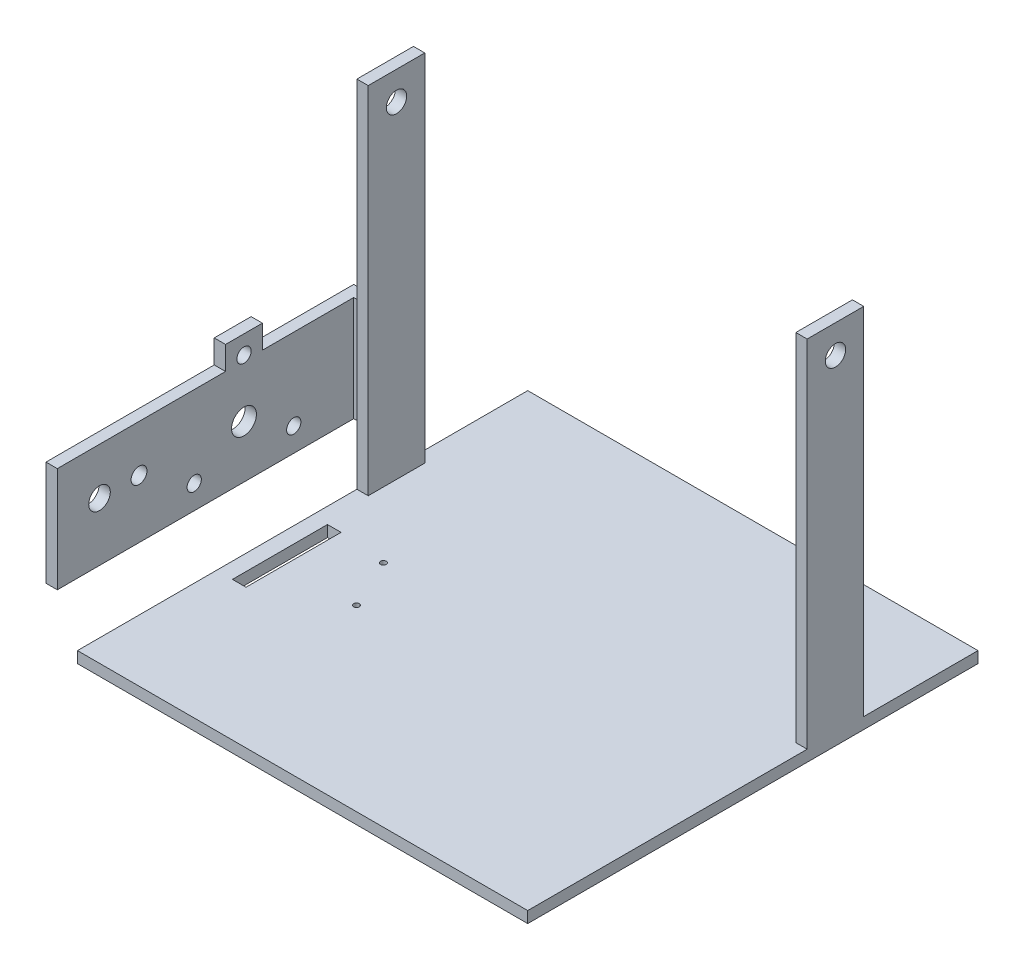
SolidWorks part; units mm, degrees
material "AISI 316 Stainless Steel Sheet (SS)"
ref_plane "Front Plane" through (0, 0, 0) normal (0, 0, 1) x (1, 0, 0)
ref_plane "Top Plane" through (0, 0, 0) normal (0, 1, 0) x (1, 0, 0)
ref_plane "Right Plane" through (0, 0, 0) normal (1, 0, 0) x (0, 0, -1)
sketch "Sketch1" plane through (0, 0, 0) normal (0, 1, 0) x (1, 0, 0)
  line L0 (0, 0) -> (199, 0)
  line L1 (199, 0) -> (199, -199)
  line L2 (199, -199) -> (0, -199)
  line L3 (0, -199) -> (0, 0)
  dimension "D1" = 199
  dimension "D2" = 199
extrude "Boss-Extrude1" add sketch "Sketch1" along normal blind 5
sketch "Sketch2" plane through (0, 5, 0) normal (0, 1, 0) x (1, 0, 0)
  line L0 (0, -50.5) -> (0, -75.5)
  line L1 (0, 0) -> (0, -199) construction
  line L2 (0, -75.5) -> (5, -75.5)
  line L3 (5, -75.5) -> (5, -50.5)
  line L4 (5, -50.5) -> (0, -50.5)
  dimension "D1" = 25
  dimension "D2" = 50.5
  dimension "D3" = 5
extrude "Boss-Extrude2" add sketch "Sketch2" along normal blind 18.8
sketch "Sketch3" plane through (0, 23.8, 0) normal (0, 1, 0) x (1, 0, 0)
  line L0 (5, -50.5) -> (5, -75.5)
  line L1 (5, -75.5) -> (5, -50.5) construction
  line L2 (5, -50.5) -> (0, -50.5) construction
  line L3 (5, -75.5) -> (0, -75.5)
  line L5 (0, -75.5) -> (0, -50.5)
  line L6 (0, -50.5) -> (5, -50.5)
  dimension "D1" = 25
extrude "Boss-Extrude3" add sketch "Sketch3" along normal blind 46.4
sketch "Sketch4" plane through (0, 70.2, 0) normal (0, 1, 0) x (1, 0, 0)
  line L0 (0, -50.5) -> (5, -50.5)
  line L1 (0, -50.5) -> (0, -75.5)
  line L2 (5, -50.5) -> (5, -75.5)
  line L3 (0, -75.5) -> (5, -75.5)
  line L4 (0, -50.5) -> (0, -75.5) construction
  line L5 (5, -50.5) -> (0, -50.5) construction
  line L6 (5, -75.5) -> (5, -50.5) construction
  dimension "D1" = 25
extrude "Boss-Extrude4" add sketch "Sketch4" along normal blind 91.8
sketch "Sketch5" plane through (0, 5, 0) normal (0, 1, 0) x (1, 0, 0)
  line L0 (199, -50.5) -> (194, -50.5)
  line L1 (199, -199) -> (199, 0) construction
  line L2 (194, -50.5) -> (194, -75.5)
  line L3 (194, -75.5) -> (199, -75.5)
  line L4 (199, -75.5) -> (199, -50.5)
  line L5 (5, -50.5) -> (0, -50.5) construction
  line L6 (0, -75.5) -> (5, -75.5) construction
  dimension "D1" = 5
extrude "Boss-Extrude5" add sketch "Sketch5" along normal blind 157
sketch "Sketch6" plane through (0, 0, 0) normal (-1, 0, 0) x (0, 0, 1)
  line L0 (75.5, 162) -> (75.5, 5) construction
  line L1 (50.5, 162) -> (75.5, 162) construction
  circle A0 centre (63, 149.5) radius 4.5
  dimension "D3" = 9
  dimension "D1" = 12.5
  dimension "D2" = 12.5
extrude "Cut-Extrude1" cut sketch "Sketch6" against normal through all
sketch "Sketch8" plane through (0, 0, 0) normal (-1, 0, 0) x (0, 0, 1)
  line L0 (63, 70.2) -> (68, 70.2)
  line L1 (68, 70.2) -> (68, 23.8)
  line L2 (68, 23.8) -> (63, 23.8)
  line L3 (63, 23.8) -> (63, 70.2)
  line L5 (75.5, 162) -> (75.5, 5) construction
  dimension "D1" = 5
  dimension "D2" = 7.5
  dimension "D3" = 46.4
extrude "Boss-Extrude6" add sketch "Sketch8" along normal blind 13.9
sketch "Sketch9" plane through (0, 0, 68) normal (0, 0, 1) x (1, 0, 0)
  line L0 (-13.9, 70.2) -> (-8.9, 70.2)
  line L1 (-13.9, 70.2) -> (-13.9, 23.8)
  line L2 (-8.9, 70.2) -> (-8.9, 23.8)
  line L3 (-13.9, 23.8) -> (-8.9, 23.8)
  line L4 (-13.9, 23.8) -> (-13.9, 70.2) construction
  line L5 (-13.9, 70.2) -> (0, 70.2) construction
  line L7 (-13.9, 23.8) -> (0, 23.8) construction
  dimension "D1" = 5
extrude "Boss-Extrude7" add sketch "Sketch9" along normal blind 131
sketch "Sketch10" plane through (-13.9, 0, 0) normal (-1, 0, 0) x (0, 0, 1)
  line L0 (63, 70.2) -> (63, 23.8) construction
  line L1 (63, 23.8) -> (199, 23.8) construction
  circle A0 centre (116.5, 47) radius 5.5
  circle A1 centre (116.5, 72.4) radius 3.15
  circle A2 centre (138.497, 34.3) radius 3.15
  circle A3 centre (94.503, 34.3) radius 3.15
  circle A4 centre (116.5, 47) radius 25.4 construction
  dimension "D1" = 11
  dimension "D3" = 6.3
  dimension "D5" = 6.3
  dimension "D6" = 6.3
  dimension "D11" = 50.8
  dimension "D2" = 53.5
  dimension "D7" = 23.2
  dimension "D10" = 12.7
sketch "Sketch11" plane through (-13.9, 0, 0) normal (-1, 0, 0) x (0, 0, 1)
  line L0 (108.35, 70.2) -> (124.65, 70.2)
  line L1 (199, 70.2) -> (63, 70.2) construction
  line L2 (124.65, 70.2) -> (124.65, 80.55)
  line L3 (124.65, 80.55) -> (108.35, 80.55)
  line L4 (108.35, 80.55) -> (108.35, 70.2)
  dimension "D1" = 8.15
  dimension "D2" = 8.15
  dimension "D3" = 8.15
extrude "Boss-Extrude8" add sketch "Sketch11" against normal blind 5
extrude "Cut-Extrude2" cut sketch "Sketch10" against normal blind 5
sketch "Sketch12" plane through (0, 5, 0) normal (0, 1, 0) x (1, 0, 0)
  line L0 (7, -95.5) -> (13, -95.5)
  line L1 (13, -95.5) -> (13, -137.5)
  line L2 (13, -137.5) -> (7, -137.5)
  line L3 (7, -137.5) -> (7, -95.5)
  line L4 (0, -75.5) -> (0, -199) construction
  line L5 (199, 0) -> (0, 0) construction
  dimension "D1" = 7
  dimension "D2" = 13
  dimension "D3" = 42
  dimension "D4" = 95.5
extrude "Cut-Extrude3" cut sketch "Sketch12" against normal blind 5
sketch "Sketch14" plane through (0, 5, 0) normal (0, 1, 0) x (1, 0, 0)
  line L0 (13, -137.5) -> (13, -95.5) construction
  circle A0 centre (34, -97.8) radius 1.25
  circle A1 centre (44.3188, -120) radius 1.25
  point P6 (13, -116.5)
  dimension "D1" = 2.5
  dimension "D2" = 2.5
  dimension "D3" = 21
  dimension "D4" = 18.7
  dimension "D5" = 3.5
  dimension "D6" = 10.3187
extrude "Cut-Extrude4" [suppressed] cut sketch "Sketch14" against normal blind 4
thread "Thread1" [suppressed] pitch 0.5 start angle 0, offset 0, length 4, pitch 0.5, diameter 2.5
ref_plane "Plane1" through (21.75, 5, 97.8) normal (0, 0, 1) x (-1, 0, 0)
sketch "Thread Profile1" plane through (21.75, 5, 97.8) normal (0, 0, 1) x (-1, 0, 0)
  line L0 (0, 0) -> (0, 0.5) construction
  line L1 (0, 0) -> (0.2706, 0.1562)
  line L2 (0.2706, 0.1562) -> (0.2706, 0.2187)
  line L3 (0.2706, 0.2187) -> (0, 0.375)
  line L4 (0.2706, 0.1875) -> (0, 0.1875) construction
  line L11 (0, 0) -> (0, 0.375)
  point P2 (0, 0)
  dimension "Pitch" = 0.5
  dimension "Profile_Angle" = 60
  dimension "Profile_Land" = 0.0625
  dimension "Profile_Height" = 0.2706
thread "Thread2" [suppressed] pitch 0.5 start angle 0, offset 0, length 4, pitch 0.5, diameter 2.5
ref_plane "Plane2" through (32.0688, 5, 120) normal (0, 0, 1) x (-1, 0, 0)
sketch "Thread Profile2" plane through (32.0688, 5, 120) normal (0, 0, 1) x (-1, 0, 0)
  line L0 (0, 0) -> (0, 0.5) construction
  line L1 (0, 0) -> (0.2706, 0.1562)
  line L2 (0.2706, 0.1562) -> (0.2706, 0.2187)
  line L3 (0.2706, 0.2187) -> (0, 0.375)
  line L4 (0.2706, 0.1875) -> (0, 0.1875) construction
  line L11 (0, 0) -> (0, 0.375)
  point P2 (0, 0)
  dimension "Pitch" = 0.5
  dimension "Profile_Angle" = 60
  dimension "Profile_Land" = 0.0625
  dimension "Profile_Height" = 0.2706
sketch "Sketch16" [suppressed] plane through (-13.9, 0, 0) normal (-1, 0, 0) x (0, 0, 1)
  circle A0 centre (180.3485, 49.5625) radius 4.7625
extrude "Cut-Extrude6" [suppressed] cut sketch "Sketch16" against normal blind 9
sketch "Sketch17" plane through (-13.9, 0, 0) normal (-1, 0, 0) x (0, 0, 1)
  circle A0 centre (162.886, 49.5625) radius 3.5
  dimension "D1" = 7
extrude "Cut-Extrude7" cut sketch "Sketch17" against normal blind 9
hole_wizard "M3x0.5 Tapped Hole1" positions "Sketch18" profile "Sketch19" tap size "M3x0.5" standard "ANSI Metric"
sketch "Sketch18" plane through (0, 5, 0) normal (0, 1, 0) x (1, 0, 0)
  point P0 (34, -97.8)
  point P3 (44.3188, -120)
sketch "Sketch19" plane through (34, 5, 97.8) normal (1, 0, 0) x (0, 0, 1)
  line L0 (0, 0) -> (0, 8.2511)
  line L1 (0, 8.2511) -> (1.25, 7.5)
  line L2 (1.25, 7.5) -> (1.25, 0)
  line L5 (1.25, 0) -> (0, 0)
  line L10 (0, 8.2511) -> (-1.25, 7.5) construction
  line L11 (0, -6.35) -> (0, 107.95) construction
  dimension "Tap Drill Dia." = 2.5
  dimension "Tap Drill Depth" = 7.5
  dimension "Drill Angle" = 118
cosmetic thread "Hole Thread1" parameters "D1"=5, "D2"=3
cosmetic thread "Hole Thread2" parameters "D1"=5, "D2"=3
sketch "Sketch20" plane through (-13.9, 0, 0) normal (-1, 0, 0) x (0, 0, 1)
  circle A0 centre (180.3485, 49.5625) radius 4.7625
extrude "Cut-Extrude8" cut sketch "Sketch20" against normal blind 10
